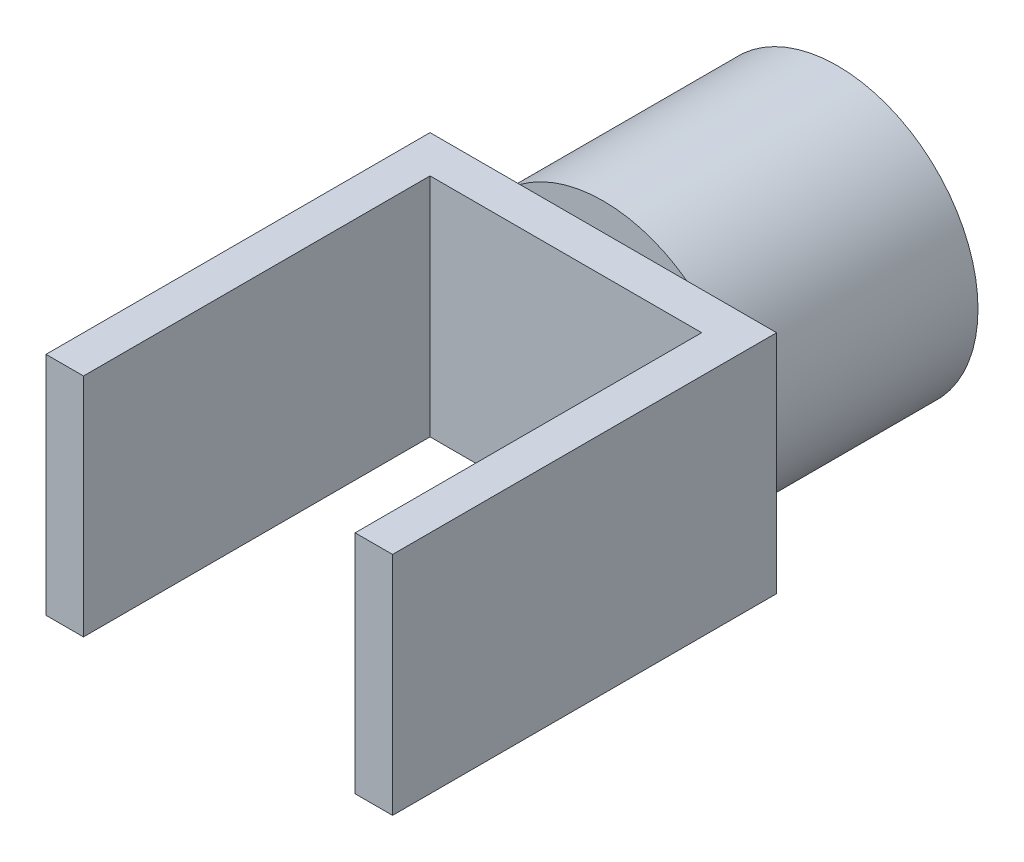
SolidWorks part; units mm, degrees
ref_plane "Plan de face" through (0, 0, 0) normal (0, 0, 1) x (1, 0, 0)
ref_plane "Plan de dessus" through (0, 0, 0) normal (0, 1, 0) x (1, 0, 0)
ref_plane "Plan de droite" through (0, 0, 0) normal (1, 0, 0) x (0, 0, -1)
sketch "Esquisse1" plane through (0, 0, 0) normal (0, 0, 1) x (1, 0, 0)
  circle A0 centre (0, 0) radius 150
  dimension "D1" = 300
extrude "Boss.-Extru.1" add sketch "Esquisse1" along normal blind 250
sketch "Esquisse2" plane through (0, 0, 0) normal (0, 0, -1) x (-1, 0, 0)
  circle A0 centre (0, 0) radius 70
  dimension "D1" = 140
extrude "Boss.-Extru.2" add sketch "Esquisse2" along normal blind 10
sketch "Esquisse3" plane through (0, 0, 250) normal (0, 0, 1) x (1, 0, 0)
  line L1 (185, -120.6546) -> (-185, -120.6546)
  line L2 (185, -120.6546) -> (185, 120.6546)
  line L3 (185, 120.6546) -> (-185, 120.6546)
  line L4 (-185, -120.6546) -> (-185, 120.6546)
  line L5 (185, -120.6546) -> (-185, 120.6546) construction
  line L6 (185, 120.6546) -> (-185, -120.6546) construction
  point P0 (0, 0)
  dimension "D1" = 370
  dimension "D2" = 241.3093
extrude "Boss.-Extru.3" add sketch "Esquisse3" along normal blind 40
sketch "Esquisse4" plane through (0, 0, 290) normal (0, 0, 1) x (1, 0, 0)
  line L0 (185, 120.6546) -> (-185, 120.6546) construction
  line L1 (-185, -120.6546) -> (-145, -120.6546)
  line L2 (-185, -120.6546) -> (-185, 120.6546)
  line L3 (-185, 120.6546) -> (-145, 120.6546)
  line L4 (-145, -120.6546) -> (-145, 120.6546)
  line L6 (185, -120.6546) -> (145, -120.6546)
  line L7 (185, -120.6546) -> (185, 120.6546)
  line L8 (185, 120.6546) -> (145, 120.6546)
  line L9 (145, -120.6546) -> (145, 120.6546)
  dimension "D1" = 40
  dimension "D2" = 40
extrude "Boss.-Extru.4" add sketch "Esquisse4" along normal blind 370
sketch "Esquisse5" plane through (145, 0, 0) normal (-1, 0, 0) x (0, 0, 1)
  line L0 (660, 120.6546) -> (660, -120.6546) construction
  line L1 (660, -120.6546) -> (290, -120.6546) construction
  circle A0 centre (560, -0.6546) radius 70
  dimension "D1" = 140
  dimension "D2" = 100
  dimension "D3" = 120
extrude "Boss.-Extru.5" add sketch "Esquisse5" along normal blind 10
